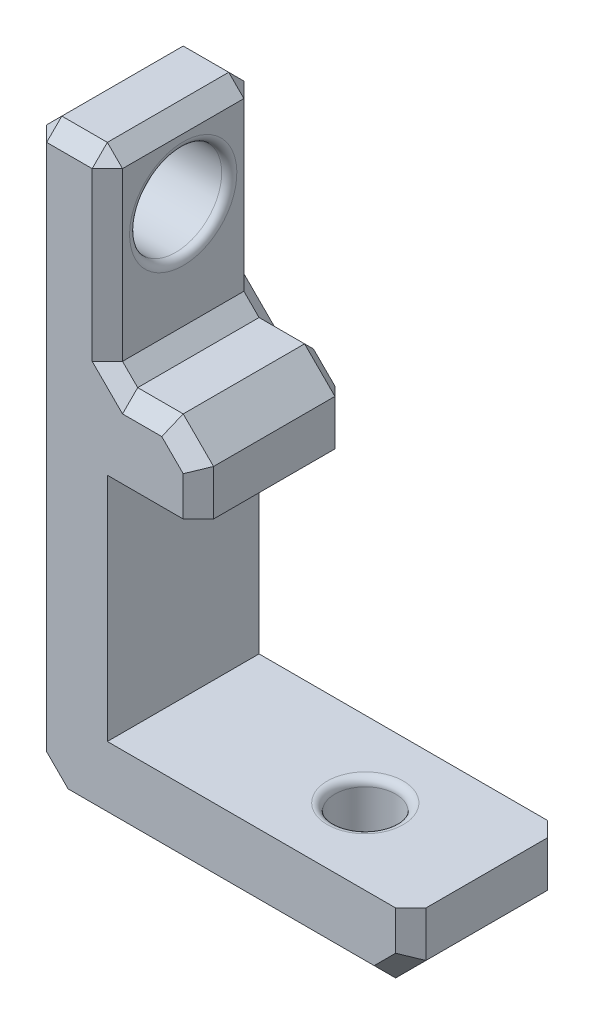
SolidWorks part; units mm, degrees
ref_plane "Plano frontal" through (0, 0, 0) normal (0, 0, 1) x (1, 0, 0)
ref_plane "Plano superior" through (0, 0, 0) normal (0, 1, 0) x (1, 0, 0)
ref_plane "Plano direito" through (0, 0, 0) normal (1, 0, 0) x (0, 0, -1)
sketch "Esboço1" plane through (0, 0, 0) normal (0, 0, 1) x (1, 0, 0)
  line L1 (-0.1136, 14.25) -> (-6.1136, 14.25)
  line L3 (-6.1136, -0.95) -> (13.8864, -0.95)
  line L4 (13.8864, -0.95) -> (13.8864, -5.95)
  line L5 (13.8864, -5.95) -> (-11.1136, -5.95)
  line L7 (-0.1136, 19.25) -> (-0.1136, 14.25)
  line L9 (-6.1136, 14.25) -> (-6.1136, -0.95)
  line L21 (-11.1136, -5.95) -> (-11.1136, 32.25)
  line L22 (-11.1136, 32.25) -> (-6.1136, 32.25)
  line L23 (-6.1136, 32.25) -> (-6.1136, 19.25)
  line L24 (-6.1136, 19.25) -> (-0.1136, 19.25)
  dimension "D1" = 5
  dimension "D2" = 20
  dimension "D3" = 15.2
  dimension "D4" = 6
  dimension "D5" = 5
  dimension "D6" = 13
  dimension "D8" = 5
extrude "Ressalto-extrusão1" add sketch "Esboço1" along normal blind 10
sketch "Esboço3" plane through (0, -5.95, 0) normal (0, -1, 0) x (1, 0, 0)
  line L0 (13.8864, 5) -> (5.8864, 5) construction
  line L1 (13.8864, 10) -> (13.8864, 0) construction
  circle A0 centre (5.8864, 5) radius 2
  dimension "D1" = 4
  dimension "D2" = 8
extrude "Corte-extrusão1" cut sketch "Esboço3" against normal blind 15
chamfer "Chanfro1" distance 1.6 angle 45 1 edges at (5.8864, -5.95, 3)
fillet "Filete1" radius 0.5 1 edges at (7.8864, -0.95, 5)
chamfer "Chanfro5" distance 2 angle 45 3 edges at (13.8864, -5.95, 5) (-0.1136, 19.25, 5) (-11.1136, -5.95, 5)
sketch "Esboço4" plane through (-6.1136, 0, 0) normal (1, 0, 0) x (0, 0, -1)
  line L2 (-10, 32.25) -> (-10, 22.25) construction
  line L3 (-10, 19.25) -> (-10, 32.25) construction
  line L4 (-10, 22.25) -> (0, 32.25) construction
  circle A0 centre (-5, 27.25) radius 3.035
  dimension "D1" = 6.07
  dimension "D2" = 10
extrude "Corte-extrusão2" cut sketch "Esboço4" against normal blind 10
fillet "Filete2" radius 0.5 2 edges at (-11.1136, 30.285, 5) (-6.1136, 30.285, 5)
chamfer "Chanfro6" distance 1 angle 45 23 edges at (-6.1136, 32.25, 5) (-8.6136, 32.25, 10) (13.8864, -2.45, 10) (12.8864, -4.95, 10) (1.3864, -5.95, 10) (-10.1136, -4.95, 10) (-11.1136, 14.15, 10) (-11.1136, 32.25, 5) (13.8864, -2.45, 0) (12.8864, -4.95, 0) (1.3864, -5.95, 0) (-10.1136, -4.95, 0) (-11.1136, 14.15, 0) (-8.6136, 32.25, 0) (-0.1136, 15.75, 0) (-1.1136, 18.25, 0) (-4.1136, 19.25, 0) (-0.1136, 15.75, 10) (-1.1136, 18.25, 10) (-4.1136, 19.25, 10) (-6.1136, 25.75, 0) (-6.1136, 19.25, 5) (-6.1136, 25.75, 10)
sketch "Esboço6" plane through (-11.1136, 0, 0) normal (-1, 0, 0) x (0, 0, 1)
  line L0 (0, 14.25) -> (10, -0.95) construction
  line L1 (5, 6.65) -> (5, 14.65) construction
  line L4 (0, 14.25) -> (0, -0.95)
  line L5 (10, 14.25) -> (0, 14.25)
  line L6 (10, -0.95) -> (10, 14.25)
  line L7 (0, -0.95) -> (10, -0.95)
  line L8 (0, 14.25) -> (0, -0.95) construction
  line L9 (10, 14.25) -> (0, 14.25) construction
  line L10 (10, -0.95) -> (10, 14.25) construction
  line L11 (0, -0.95) -> (10, -0.95) construction
  circle A0 centre (5, 6.65) radius 0.9
  circle A1 centre (5, 14.65) radius 0.9
  point P8 (4.7514, 16.7741)
  dimension "D2" = 1.8
  dimension "D3" = 1.8
  dimension "D4" = 8
  dimension "D1" = 0
extrude "Corte-extrusão3" cut sketch "Esboço6" against normal blind 3.5
